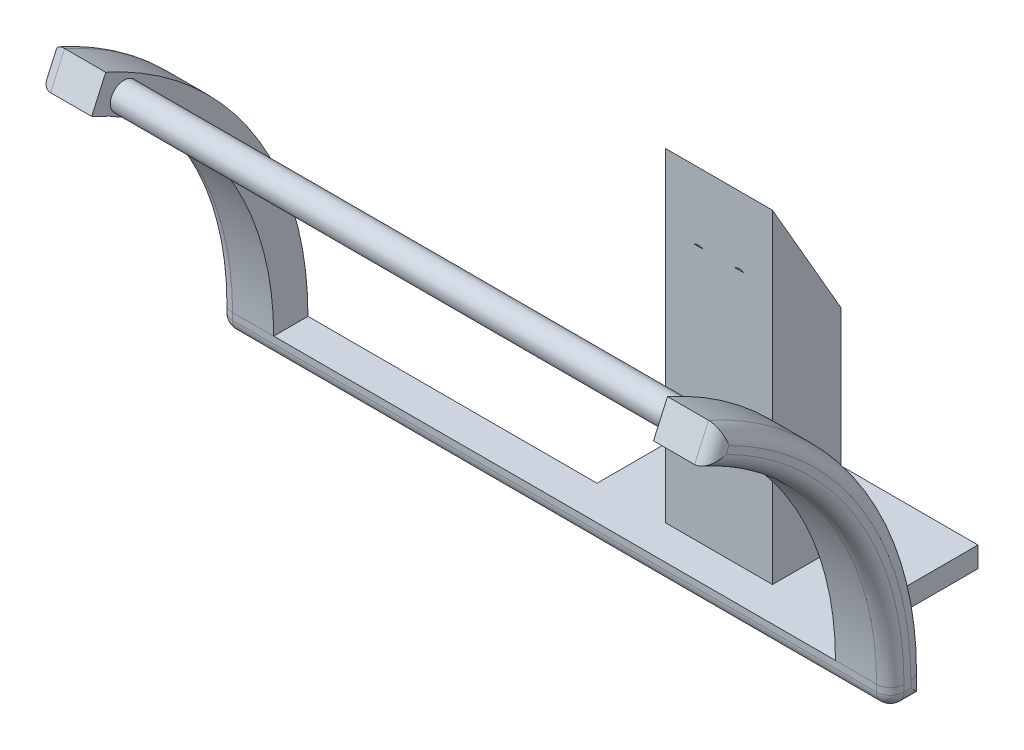
SolidWorks part; units mm, degrees
ref_plane "Front Plane" through (0, 0, 0) normal (0, 0, 1) x (1, 0, 0)
ref_plane "Top Plane" through (0, 0, 0) normal (0, 1, 0) x (1, 0, 0)
ref_plane "Right Plane" through (0, 0, 0) normal (1, 0, 0) x (0, 0, -1)
sketch "Sketch1" plane through (0, 0, 0) normal (0, 1, 0) x (1, 0, 0)
  line L0 (-8.4368, 20.25) -> (-8.4368, 0.25) construction
  line L1 (-26.2418, 20.25) -> (9.3682, 20.25)
  line L2 (-26.2418, 20.25) -> (-26.2418, 0.25)
  line L3 (-26.2418, 0.25) -> (9.3682, 0.25)
  line L4 (9.3682, 20.25) -> (9.3682, 0.25)
  line L5 (-38.4368, 0.25) -> (21.5632, 0.25)
  line L6 (-38.4368, 0.25) -> (-38.4368, -4.75)
  line L7 (-38.4368, -4.75) -> (21.5632, -4.75)
  line L8 (21.5632, 0.25) -> (21.5632, -4.75)
  line L9 (-23.1313, 20.25) -> (6.2616, 20.25) construction
  line L11 (-38.4368, -4.75) -> (-76.4368, -4.75)
  line L12 (-38.4368, -4.75) -> (-38.4368, 0.25)
  line L13 (-38.4368, 0.25) -> (-76.4368, 0.25)
  line L14 (-76.4368, -4.75) -> (-76.4368, 0.25)
  point P10 (-8.4368, 0.25)
  dimension "D1" = 20
  dimension "D2" = 35.61
  dimension "D3" = 60
  dimension "D4" = 5
  dimension "D5" = 38
extrude "Boss-Extrude1" add sketch "Sketch1" along normal blind 3 contours L8 L5 L3 L6 L7 | L1 L0 L5 L4 | L0 L1 L2 L3 | L12 L11 L14 L13
ref_plane "Plane1" through (21.5632, 0, 0) normal (1, 0, 0) x (0, 0, -1)
sketch "Sketch2" plane through (21.5632, 0, 0) normal (1, 0, 0) x (0, 0, -1)
  line L0 (-4.75, 3) -> (-34.75, 3) construction
  line L1 (-34.75, 3) -> (-49.75, 3) construction
  line L2 (-29.2678, 48.6123) -> (-31.316, 44.051)
  line L3 (-4.75, 3) -> (0.25, 3)
  circle A0 centre (-49.75, 3) radius 15 construction
  arc A1 (-4.75, 3) -> (-31.316, 44.051) centre (-49.75, 3) ccw
  arc A2 (0.25, 3) -> (-29.2678, 48.6123) centre (-49.75, 3) ccw
  dimension "D3" = 30
  dimension "D1" = 30
  dimension "D2" = 15
ref_plane "Plane2" through (-8.4368, 0, 0) normal (1, 0, 0) x (0, 0, -1)
sketch "Sketch3" plane through (0, 0, 0) normal (0, -1, 0) x (1, 0, 0)
  circle A0 centre (-20.4847, -8.75) radius 1.5
  circle A1 centre (-8.4349, -16.25) radius 1.5
  circle A2 centre (3.6149, -8.75) radius 1.5
  dimension "D1" = 3
extrude "Cut-Extrude1" cut sketch "Sketch3" against normal blind 5
sketch "Sketch7" plane through (0, 3, 0) normal (0, 1, 0) x (1, 0, 0)
  line L0 (-26.2418, 20.25) -> (-26.2418, 0.25) construction
  line L1 (-16.2418, 10.25) -> (-0.6318, 10.25)
  line L2 (-16.2418, 10.25) -> (-16.2418, 0.25)
  line L3 (-16.2418, 0.25) -> (-0.6318, 0.25)
  line L4 (-0.6318, 10.25) -> (-0.6318, 0.25)
  line L5 (9.3682, 20.25) -> (9.3682, 0.25) construction
  line L6 (-38.4368, -4.75) -> (21.5632, -4.75) construction
  dimension "D1" = 10
  dimension "D2" = 10
  dimension "D3" = 5
  dimension "D4" = 10
extrude "Boss-Extrude4" add sketch "Sketch7" along normal blind 30
sketch "Sketch8" plane through (-16.2418, 0, 0) normal (-1, 0, 0) x (0, 0, 1)
  line L0 (-10.25, 33) -> (-0.25, 50.3205)
  line L1 (-0.25, 33) -> (-0.25, 50.3205)
  line L2 (-10.25, 33) -> (-0.25, 33) construction
  line L3 (-10.25, 33) -> (-0.25, 33)
  dimension "D1" = 60
extrude "Boss-Extrude5" add sketch "Sketch8" against normal up to surface (15.61 mm away) up to face at (-0.6318, 18, -5.25)
sketch "Sketch9" plane through (0, 12.6884, -21.9769) normal (0, 0.5, -0.866) x (1, 0, 0)
  line L0 (-16.2418, -33.4538) -> (-0.6318, -33.4538) construction
  line L1 (-16.2418, -43.4538) -> (-16.2418, -23.4538) construction
  line L2 (-0.6318, -23.4538) -> (-0.6318, -43.4538) construction
  line L3 (-8.4368, -23.4538) -> (-8.4368, -43.4538) construction
  line L4 (-0.6318, -23.4538) -> (-16.2418, -23.4538) construction
  line L5 (-0.6318, -43.4538) -> (-16.2418, -43.4538) construction
  circle A0 centre (-11.4368, -33.4538) radius 1.5
  circle A1 centre (-5.4368, -33.4538) radius 1.5
  dimension "D1" = 3
  dimension "D2" = 3
  dimension "D3" = 6
  dimension "D4" = 3
extrude "Cut-Extrude2" cut sketch "Sketch9" against normal blind 5
extrude "Boss-Extrude6" add sketch "Sketch2" against normal blind 8
ref_plane "Plane3" through (-27.4368, 0, 0) normal (-1, 0, 0) x (0, 0, 1)
mirror "Mirror1" about plane through (-27.4368, 0, 0) normal (-1, 0, 0) of "Boss-Extrude6"
fillet "Fillet4" radius 2 13 edges at (-76.4368, 1.5, -0.25) (-76.4368, 30.1651, 7.7732) (-76.4368, 46.3317, 30.2919) (-76.4368, 27.4486, 11.9708) (-76.4368, 1.5, 4.75) (-76.4368, 0, 2.25) (21.5632, 1.5, 4.75) (21.5632, 27.4486, 11.9708) (21.5632, 46.3317, 30.2919) (21.5632, 30.1651, 7.7732) (21.5632, 1.5, -0.25) (21.5632, 0, 2.25) (-27.4368, 0, 4.75)
sketch "Sketch10" plane through (-68.4368, 0, 0) normal (1, 0, 0) x (0, 0, -1)
  line L0 (-21.8913, 44.5198) -> (-23.9724, 39.8852)
  line L1 (-31.316, 44.051) -> (-21.8913, 44.5198) construction
  line L2 (-4.75, 3) -> (0.25, 3)
  line L3 (-29.2678, 48.6123) -> (-31.316, 44.051)
  line L4 (-4.75, 3) -> (0.25, 3)
  line L5 (-29.2678, 48.6123) -> (-31.316, 44.051)
  line L6 (-23.9724, 39.8852) -> (-29.2678, 48.6123) construction
  circle A0 centre (-26.6036, 44.2854) radius 2
  arc A2 (-4.75, 3) -> (-31.316, 44.051) centre (-49.75, 3) ccw
  arc A3 (0.25, 3) -> (-29.2678, 48.6123) centre (-49.75, 3) ccw
  arc A4 (-4.75, 3) -> (-31.316, 44.051) centre (-49.75, 3) ccw
  arc A5 (0.25, 3) -> (-29.2678, 48.6123) centre (-49.75, 3) ccw
  dimension "D2" = 4
  dimension "D1" = 0
extrude "Boss-Extrude7" add sketch "Sketch10" along normal up to surface (82 mm away) contours A0 up to face at (13.5632, 26.7364, 13.0715)
